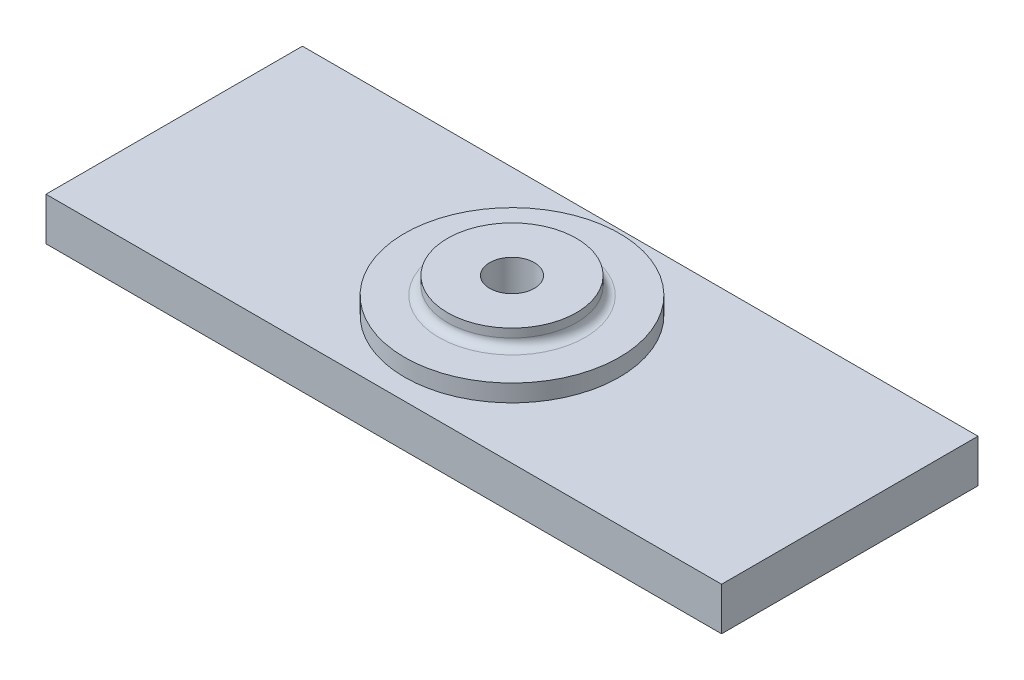
SolidWorks part; units mm, degrees
ref_plane "前视基准面" through (0, 0, 0) normal (0, 0, 1) x (1, 0, 0)
ref_plane "上视基准面" through (0, 0, 0) normal (0, 1, 0) x (1, 0, 0)
ref_plane "右视基准面" through (0, 0, 0) normal (1, 0, 0) x (0, 0, -1)
sketch "草图1" plane through (0, 0, 0) normal (0, 1, 0) x (1, 0, 0)
  circle A0 centre (0, 0) radius 12.5
  dimension "D1" = 25
extrude "凸台-拉伸1" add sketch "草图1" along normal blind 2
sketch "草图2" plane through (0, 2, 0) normal (0, 1, 0) x (1, 0, 0)
  circle A0 centre (0, 0) radius 7.5
  dimension "D1" = 15
extrude "凸台-拉伸2" add sketch "草图2" along normal blind 2
fillet "圆角1" radius 1 1 edges at (0, 2, 7.5)
sketch "草图3" plane through (0, 4, 0) normal (0, 1, 0) x (1, 0, 0)
  circle A0 centre (0, 0) radius 2.6
  dimension "D1" = 5.2
extrude "切除-拉伸1" cut sketch "草图3" against normal up to next
sketch "草图4" plane through (0, 0, 0) normal (0, 1, 0) x (1, 0, 0)
  line L1 (-39.3043, -14.9196) -> (39.3043, -14.9196)
  line L2 (-39.3043, -14.9196) -> (-39.3043, 14.9196)
  line L3 (-39.3043, 14.9196) -> (39.3043, 14.9196)
  line L4 (39.3043, -14.9196) -> (39.3043, 14.9196)
  line L5 (-39.3043, -14.9196) -> (39.3043, 14.9196) construction
  line L6 (-39.3043, 14.9196) -> (39.3043, -14.9196) construction
  point P0 (0, 0)
extrude "凸台-拉伸3" add sketch "草图4" against normal blind 5
sketch "草图5" plane through (0, 0, 0) normal (0, 0, 1) x (1, 0, 0)
  line L0 (0, 0) -> (0, 4) construction
  line L1 (2.6, 4) -> (-2.6, 4) construction
